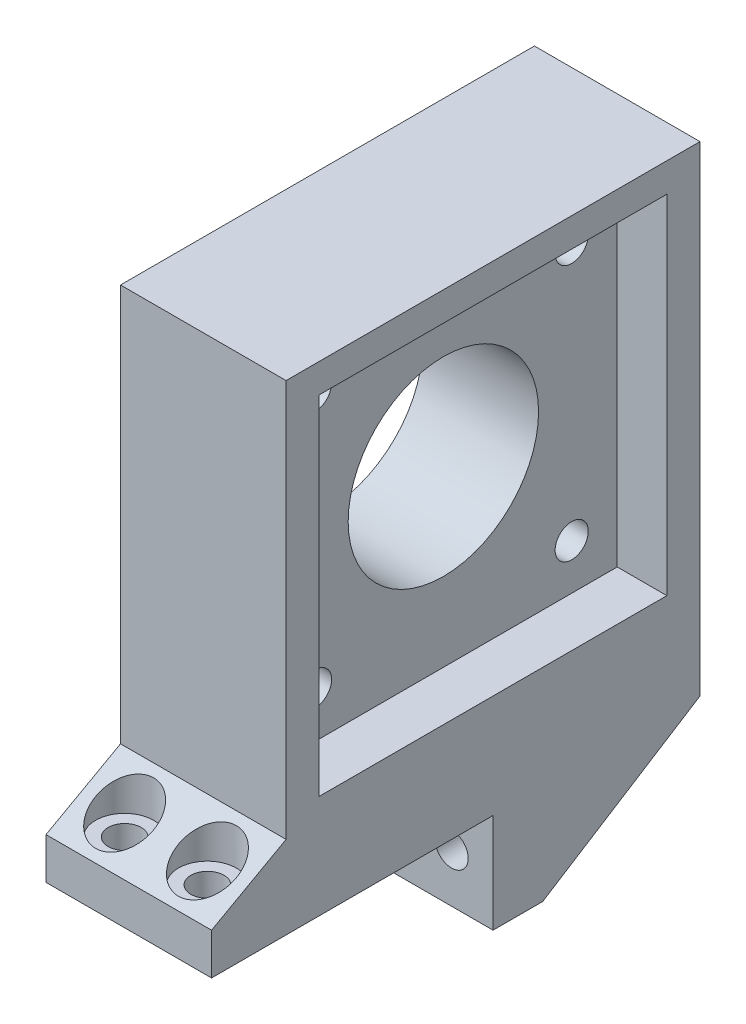
SolidWorks part; units mm, degrees
ref_plane "Front Plane" through (0, 0, 0) normal (0, 0, 1) x (1, 0, 0)
ref_plane "Top Plane" through (0, 0, 0) normal (0, 1, 0) x (1, 0, 0)
ref_plane "Right Plane" through (0, 0, 0) normal (1, 0, 0) x (0, 0, -1)
sketch "Sketch1" plane through (0, 0, 0) normal (0, 1, 0) x (1, 0, 0)
  line L1 (0, 0) -> (-20, 0)
  line L2 (0, 0) -> (0, -50)
  line L3 (0, -50) -> (-20, -50)
  line L4 (-20, 0) -> (-20, -50)
  dimension "D1" = 20
  dimension "D2" = 50
extrude "Boss-Extrude1" add sketch "Sketch1" along normal blind 70
sketch "Sketch2" plane through (0, 0, 0) normal (1, 0, 0) x (0, 0, -1)
  line L0 (-50, 70) -> (0, 70) construction
  line L1 (0, 70) -> (0, 0) construction
  line L2 (0, 45.5) -> (-50, 45.5) construction
  line L3 (-25, 70) -> (-25, 0) construction
  line L4 (-25, 70) -> (-25, 0) construction
  line L7 (-50, 70) -> (-50, 0) construction
  circle A0 centre (-9.5, 61) radius 2
  circle A4 centre (-25, 45.5) radius 11.5
  circle A5 centre (-9.5, 30) radius 2
  circle A8 centre (-40.5, 30) radius 2
  circle A9 centre (-40.5, 61) radius 2
  dimension "D1" = 4
  dimension "D2" = 9
  dimension "D3" = 15.5
  dimension "D6" = 23
  dimension "D7" = 0
  dimension "D8" = 0
  dimension "D4" = 15.5
  dimension "D5" = 0
extrude "Cut-Extrude2" cut sketch "Sketch2" against normal blind 60
sketch "Sketch4" plane through (0, 0, 0) normal (1, 0, 0) x (0, 0, -1)
  line L1 (-50, 0) -> (-25, 0)
  line L2 (-50, 0) -> (-50, 12)
  line L3 (-50, 12) -> (-25, 12)
  line L4 (-25, 0) -> (-25, 12)
  circle A0 centre (-25, 45.5) radius 11.5 construction
  dimension "D1" = 12
  dimension "D2" = 0
extrude "Cut-Extrude3" cut sketch "Sketch4" against normal blind 60
sketch "Sketch8" plane through (0, 0, 0) normal (0, 0, -1) x (-1, 0, 0)
  line L0 (0, 0) -> (20, 0) construction
  line L1 (20, 70) -> (20, 0) construction
  line L2 (0, 70) -> (0, 0) construction
  circle A0 centre (15, 6) radius 2
  circle A1 centre (5, 6) radius 2
  dimension "D1" = 4
  dimension "D2" = 6
  dimension "D3" = 5
  dimension "D4" = 4
  dimension "D5" = 0
  dimension "D6" = 5
extrude "Cut-Extrude5" cut sketch "Sketch8" against normal blind 15
sketch "Sketch9" plane through (0, 0, 0) normal (1, 0, 0) x (0, 0, -1)
  line L0 (0, 50) -> (-50, 41) construction
  line L1 (-4, 66.5) -> (-46, 66.5)
  line L2 (-4, 66.5) -> (-4, 24.5)
  line L3 (-4, 24.5) -> (-46, 24.5)
  line L4 (-46, 66.5) -> (-46, 24.5)
  line L5 (0, 70) -> (0, 0) construction
  line L6 (-50, 70) -> (-50, 12) construction
  line L7 (-25, 70) -> (-25, 12) construction
  line L8 (-50, 70) -> (0, 70) construction
  line L9 (-25, 12) -> (-50, 12) construction
  circle A0 centre (-25, 45.5) radius 11.5 construction
  dimension "D1" = 0
  dimension "D2" = 42
  dimension "D3" = 21
  dimension "D4" = 42
  dimension "D5" = 21
  dimension "D6" = 0
extrude "Cut-Extrude6" cut sketch "Sketch9" against normal blind 6
sketch "Sketch11" plane through (0, 0, 0) normal (1, 0, 0) x (0, 0, -1)
  line L7 (-19, 0) -> (0, 0)
  line L8 (-25, 0) -> (0, 0) construction
  line L9 (0, 0) -> (0, 12)
  line L10 (0, 70) -> (0, 0) construction
  line L11 (0, 12) -> (-19, 0)
  line L12 (-25, 12) -> (-50, 12) construction
  dimension "D1" = 0
  dimension "D2" = 6
extrude "Cut-Extrude8" cut sketch "Sketch11" against normal blind 30
sketch "Sketch12" plane through (0, 0, 50) normal (0, 0, 1) x (1, 0, 0)
  line L0 (-20, 70) -> (-20, 12) construction
  line L1 (0, 12) -> (-20, 12)
  line L2 (0, 12) -> (0, 17)
  line L3 (0, 17) -> (-20, 17)
  line L4 (-20, 12) -> (-20, 17)
  dimension "D1" = 5
extrude "Boss-Extrude2" add sketch "Sketch12" along normal blind 9
sketch "Sketch14" plane through (0, 0, 0) normal (1, 0, 0) x (0, 0, -1)
  line L0 (-50, 17) -> (-59, 17)
  line L2 (-59, 17) -> (-50, 22)
  line L3 (-50, 70) -> (-50, 17) construction
  line L4 (-50, 22) -> (-50, 17)
  line L6 (-59, 17) -> (-59, 12) construction
  point P3 (0, 0)
  point P8 (0, 0)
  dimension "D1" = 5
  dimension "D2" = 0
extrude "Boss-Extrude3" add sketch "Sketch14" against normal up to vertex (20 mm away)
sketch "Sketch15" plane through (0, 12, 0) normal (0, -1, 0) x (-1, 0, 0)
  line L0 (0, -25) -> (0, -59) construction
  line L1 (20, -25) -> (20, -59) construction
  line L2 (20, -59) -> (0, -59) construction
  circle A0 centre (5, -54.5) radius 2
  circle A1 centre (15, -54.5) radius 2
  dimension "D1" = 4
  dimension "D2" = 4
  dimension "D3" = 5
  dimension "D4" = 5
  dimension "D5" = 4.5
  dimension "D6" = 4.5
extrude "Cut-Extrude9" cut sketch "Sketch15" against normal blind 10
sketch "Sketch17" plane through (0, 0, 0) normal (0, 0, -1) x (-1, 0, 0)
  circle A0 centre (15, 6) radius 3.5
  circle A1 centre (5, 6) radius 3.5
  dimension "D1" = 7
  dimension "D2" = 7
sketch "Sketch18" plane through (0, 70, 0) normal (0, 1, 0) x (1, 0, 0)
  circle A0 centre (-15, -54.5) radius 3.5
  circle A1 centre (-5, -54.5) radius 3.5
  dimension "D1" = 7
  dimension "D2" = 7
extrude "Cut-Extrude12" cut sketch "Sketch18" against normal blind 53
extrude "Cut-Extrude13" cut sketch "Sketch17" against normal blind 16
sketch "Sketch19" plane through (0, 0, 16) normal (0, 0, -1) x (-1, 0, 0)
  circle A0 centre (5, 6) radius 2
  circle A1 centre (15, 6) radius 2
  dimension "D1" = 4
  dimension "D2" = 4
extrude "Cut-Extrude14" cut sketch "Sketch19" against normal blind 25
